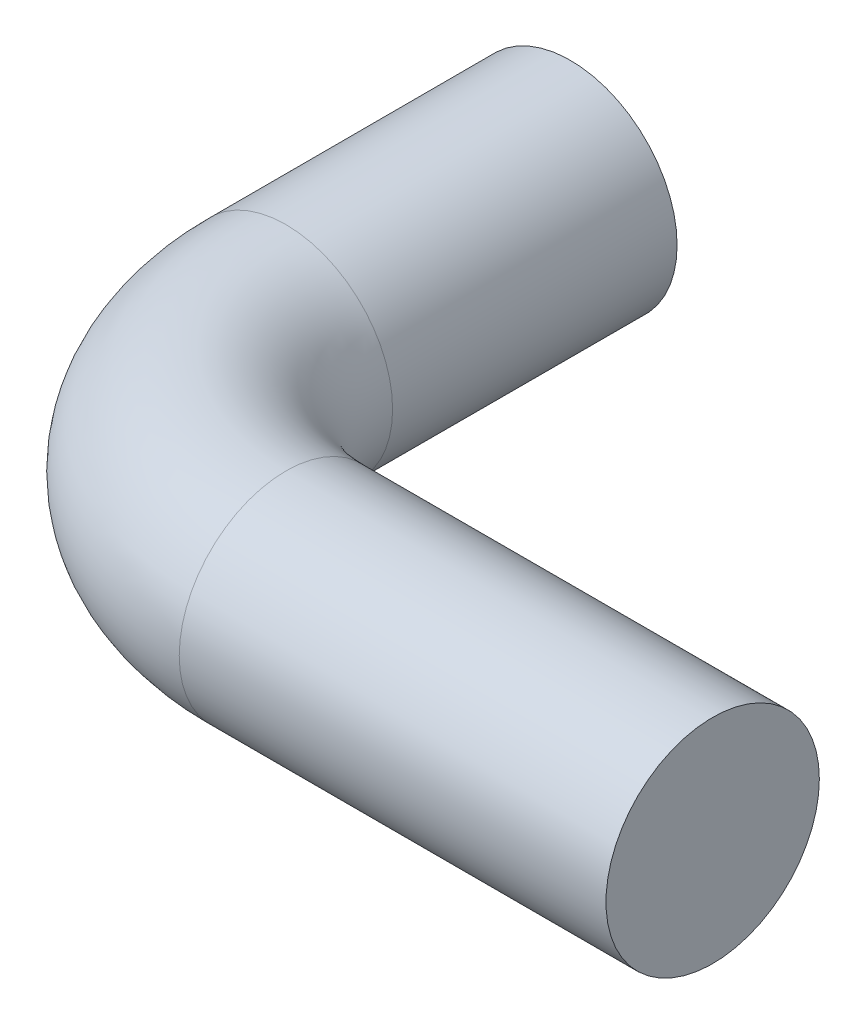
SolidWorks part; units mm, degrees
ref_plane "Front Plane" through (0, 0, 0) normal (0, 0, 1) x (1, 0, 0)
ref_plane "Top Plane" through (0, 0, 0) normal (0, 1, 0) x (1, 0, 0)
ref_plane "Right Plane" through (0, 0, 0) normal (1, 0, 0) x (0, 0, -1)
sketch "Sketch2" plane through (0, 0, 0) normal (0, 1, 0) x (1, 0, 0)
  line L0 (0, 0) -> (150, 0)
  line L1 (-75, 175) -> (-75, 75)
  arc A0 (-75, 75) -> (0, 0) centre (0, 75) ccw
  dimension "D1" = 150
  dimension "D2" = 75
  dimension "D3" = 75
  dimension "D4" = 100
sketch "Sketch3" plane through (0, 0, 0) normal (1, 0, 0) x (0, 0, -1)
  circle A0 centre (0, 0) radius 37.5
  dimension "D1" = 75
sweep "Sweep1" add path "Sketch2" circular profile diameter 75 parameters "D3"=75
